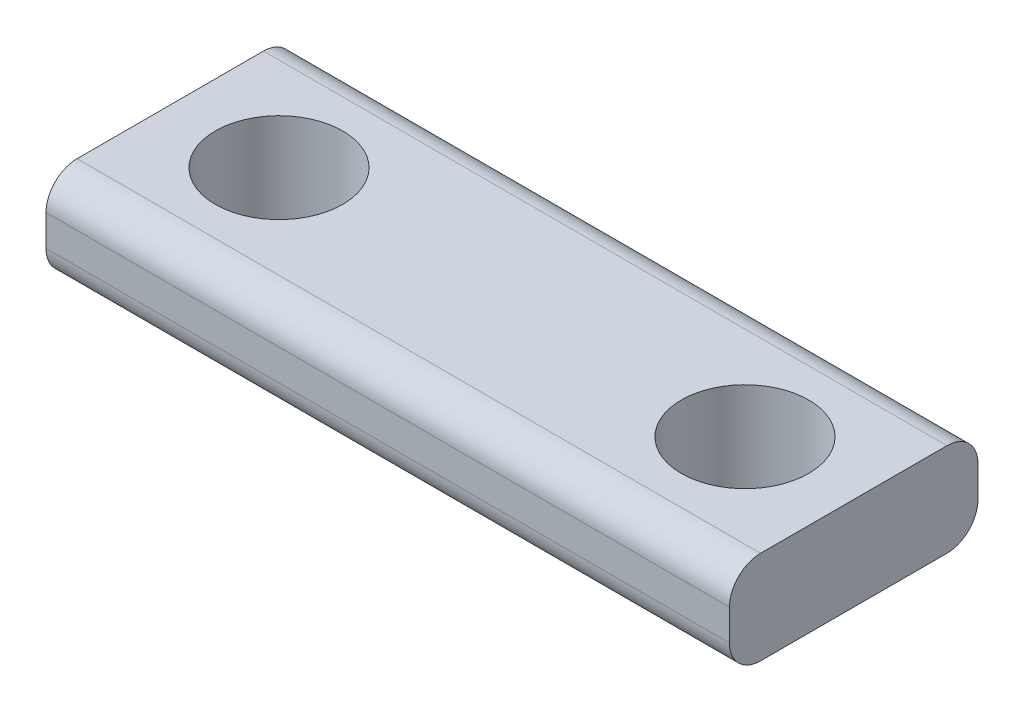
SolidWorks part; units mm, degrees
material "AISI 304"
ref_plane "Front Plane" through (0, 0, 0) normal (0, 0, 1) x (1, 0, 0)
ref_plane "Top Plane" through (0, 0, 0) normal (0, 1, 0) x (1, 0, 0)
ref_plane "Right Plane" through (0, 0, 0) normal (1, 0, 0) x (0, 0, -1)
sketch "Sketch1" plane through (0, 0, 0) normal (0, 1, 0) x (1, 0, 0)
  line L0 (3.5, 4) -> (18.5, 4) construction
  line L1 (0, 0) -> (22, 0)
  line L2 (0, 0) -> (0, 8)
  line L3 (0, 8) -> (22, 8)
  line L4 (22, 0) -> (22, 8)
  line L5 (11, 4) -> (11, 8) construction
  circle A0 centre (3.5, 4) radius 2.05
  circle A1 centre (18.5, 4) radius 2.05
  dimension "D3" = 4.1
  dimension "D1" = 8
  dimension "D2" = 22
  dimension "D4" = 4
  dimension "D5" = 15
extrude "Boss-Extrude1" add sketch "Sketch1" along normal blind 3
fillet "Fillet1" radius 1 4 edges at (11, 0, 0) (11, 0, -8) (11, 3, -8) (11, 3, 0)
